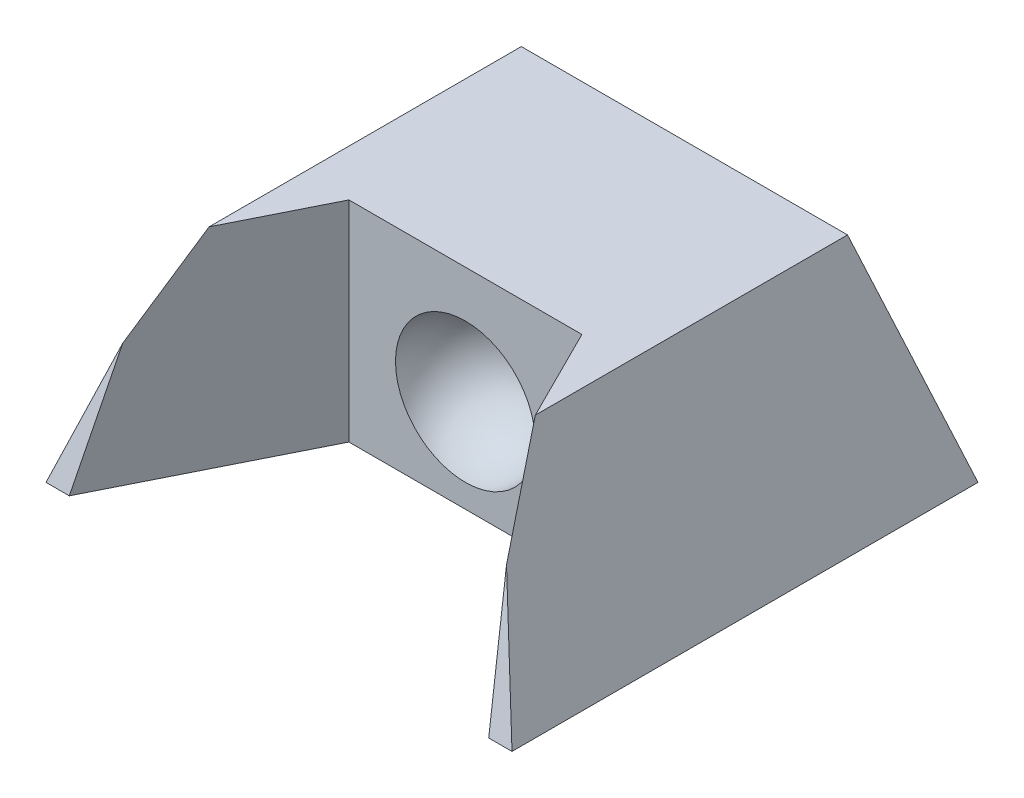
SolidWorks part; units mm, degrees
ref_plane "Ebene vorne" through (0, 0, 0) normal (0, 0, 1) x (1, 0, 0)
ref_plane "Ebene oben" through (0, 0, 0) normal (0, 1, 0) x (1, 0, 0)
ref_plane "Ebene rechts" through (0, 0, 0) normal (1, 0, 0) x (0, 0, -1)
sketch "Skizze1" plane through (0, 0, 0) normal (0, 0, 1) x (1, 0, 0)
  line L0 (0, 0) -> (100, 0)
  line L1 (100, 0) -> (85, 45)
  line L2 (85, 45) -> (15, 45)
  line L3 (15, 45) -> (0, 0)
  dimension "D1" = 100
  dimension "D2" = 15
  dimension "D3" = 15
  dimension "D4" = 45
extrude "Grundkörper" add sketch "Skizze1" against normal blind 100
sketch "Skizze2" plane through (0, 0, 0) normal (1, 0, 0) x (0, 0, -1)
  line L0 (100, 0) -> (87, 45)
  line L1 (100, 45) -> (0, 45) construction
  line L2 (87, 45) -> (100, 45)
  line L3 (100, 45) -> (100, 0)
  dimension "D1" = 13
extrude "Schraegen_vorne" cut sketch "Skizze2" along normal blind 100
ref_plane "Ebene1" through (0, 0, -50) normal (0, 0, 1) x (1, 0, 0)
mirror "Spiegel_Schraege_hinten" about plane through (0, 0, -50) normal (0, 0, 1) of "Schraegen_vorne"
sketch "Skizze4" plane through (0, 0, 0) normal (0, -1, 0) x (1, 0, 0)
  line L7 (5, 0) -> (95, 0)
  line L8 (0, 0) -> (100, 0) construction
  line L9 (95, 0) -> (75, -40)
  line L10 (75, -40) -> (25, -40)
  line L11 (25, -40) -> (5, 0)
  dimension "D1" = 90
  dimension "D2" = 50
  dimension "D3" = 20
  dimension "D4" = 5
  dimension "D5" = 40
extrude "Schnitt-Linear austragen4" cut sketch "Skizze4" against normal blind 45
sketch "Skizze5" plane through (0, 0, -40) normal (0, 0, 1) x (1, 0, 0)
  circle A0 centre (50, 20) radius 15
ref_axis "Achse1" through (50, 20, -127.8909) along (0, 0, 1)
ref_plane "Ebene2" through (50, 0, 0) normal (-1, 0, 0) x (0, 0, 1)
sketch "Skizze6" plane through (50, 0, 0) normal (-1, 0, 0) x (0, 0, 1)
  line L0 (-40, 5) -> (-40, 35) construction
  line L1 (-55, 20) -> (-40, 20)
  line L2 (-40, 20) -> (-40, 5)
  arc A0 (-40, 5) -> (-55, 20) centre (-40, 20) cw
revolve "Schnitt-Rotation1" cut sketch "Skizze6" angle 360 about axis through (50, 20, -127.8909) along (0, 0, 1)
shell "Wandung1" thickness 1.75
